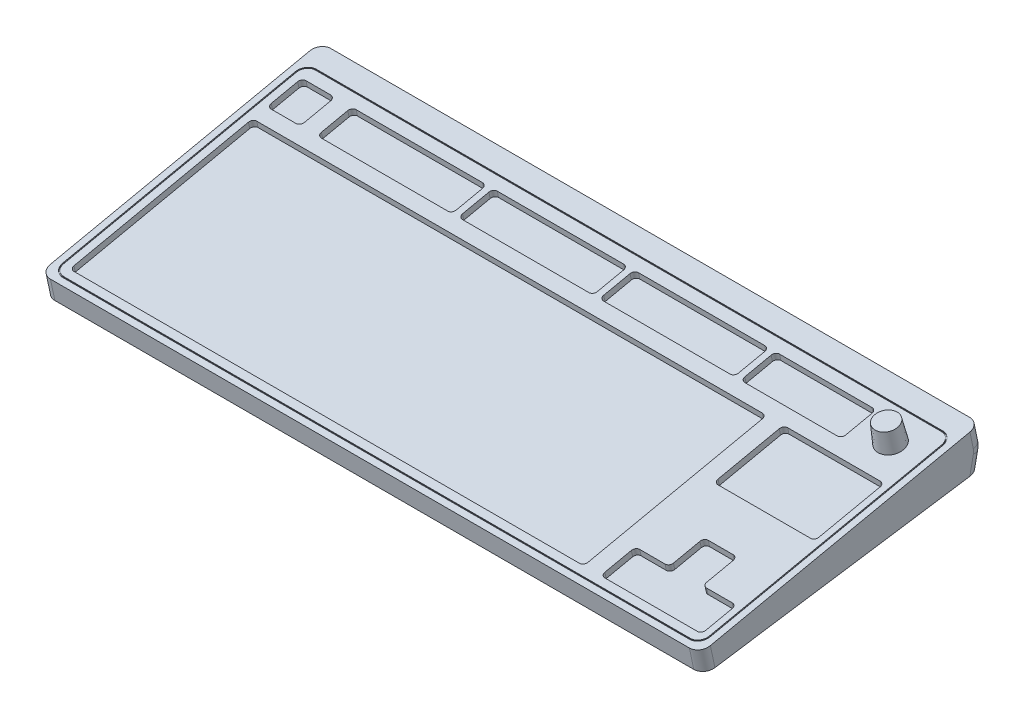
SolidWorks part; units mm, degrees
other "Camera1"
material "ABS"
ref_plane "Front Plane" through (0, 0, 0) normal (0, 0, 1) x (1, 0, 0)
ref_plane "Top Plane" through (0, 0, 0) normal (0, 1, 0) x (1, 0, 0)
ref_plane "Right Plane" through (0, 0, 0) normal (1, 0, 0) x (0, 0, -1)
sketch "Sketch1" plane through (0, 0, 0) normal (0, 1, 0) x (1, 0, 0)
  line L0 (0, 0) -> (128.8917, 0) construction
ref_plane "Plane1" through (0, 0, 0) normal (0, 0.9781, 0.2079) x (1, 0, 0)
sketch "Sketch2" plane through (0, 0, 0) normal (0, 0.9781, 0.2079) x (1, 0, 0)
  line L1 (0, 0) -> (311, 0)
  line L2 (0, 0) -> (0, 135)
  line L3 (0, 135) -> (311, 135)
  line L4 (311, 0) -> (311, 135)
  dimension "D1" = 135
  dimension "D2" = 311
extrude "Boss-Extrude1" add sketch "Sketch2" against normal blind 10
sketch "Sketch5" plane through (0, 0, 0) normal (-1, 0, 0) x (0, 0, 1)
  line L0 (-134.129, 18.2866) -> (-132.3992, 9.7621)
  line L1 (-132.3992, 9.7621) -> (-2.0791, -9.7815)
  line L2 (-2.0791, -9.7815) -> (-134.129, 18.2866)
  dimension "D1" = 110
extrude "Boss-Extrude2" add sketch "Sketch5" against normal blind 311
fillet "Fillet1" radius 10 1 edges at (155.5, 18.2866, -134.129)
fillet "Fillet2" radius 5 8 edges at (0, 13.0064, -133.0575) (311, 13.0064, -133.0575) (311, 18.2856, -133.9155) (0, 18.2856, -133.9155) (311, 24.1933, -132.8735) (0, 24.1933, -132.8735) (311, -4.8907, -1.0396) (0, -4.8907, -1.0396)
sketch "Sketch6" plane through (0, 0, 0) normal (0, 0.9781, 0.2079) x (1, 0, 0)
  line L0 (306, 135) -> (5, 135) construction
  line L5 (8, 3) -> (303, 3)
  line L6 (3, 8) -> (3, 120)
  line L7 (8, 125) -> (303, 125)
  line L8 (308, 8) -> (308, 120)
  line L9 (311, 5) -> (311, 130) construction
  line L10 (0, 130) -> (0, 5) construction
  line L11 (0, 0) -> (128.8917, 0) construction
  arc A2 (15, 10) -> (10, 15) centre (15, 15) cw
  arc A4 (303, 125) -> (308, 120) centre (303, 120) cw
  arc A5 (303, 3) -> (308, 8) centre (303, 8) ccw
  arc A6 (8, 3) -> (3, 8) centre (8, 8) cw
  arc A7 (3, 120) -> (8, 125) centre (8, 120) cw
  dimension "D2" = 3
  dimension "D5" = 5
  dimension "D1" = 10
  dimension "D3" = 3
  dimension "D4" = 3
extrude "Cut-Extrude-Thin1" cut sketch "Sketch6" against normal blind 0.5 thin thin type one direction reverse wall 0.5
sketch "Sketch7" plane through (0, 0, 0) normal (0, 0.9781, 0.2079) x (1, 0, 0)
  line L0 (306, 135) -> (5, 135) construction
  line L1 (9, 119) -> (20.6, 119)
  line L2 (7, 117) -> (7, 104.3)
  line L3 (9, 102.3) -> (20.6, 102.3)
  line L4 (22.6, 117) -> (22.6, 104.3)
  line L5 (0, 130) -> (0, 5) construction
  line L6 (302.6, 24.05) -> (290.675, 24.05)
  line L7 (32.6, 119) -> (92.1, 119)
  line L8 (30.6, 117) -> (30.6, 104.3)
  line L9 (32.6, 102.3) -> (92.1, 102.3)
  line L10 (94.1, 117) -> (94.1, 104.3)
  line L11 (99.1, 119) -> (158.6, 119)
  line L12 (97.1, 117) -> (97.1, 104.3)
  line L13 (99.1, 102.3) -> (158.6, 102.3)
  line L14 (160.6, 117) -> (160.6, 104.3)
  line L15 (165.6, 119) -> (225.1, 119)
  line L16 (163.6, 117) -> (163.6, 104.3)
  line L17 (165.6, 102.3) -> (225.1, 102.3)
  line L18 (227.1, 117) -> (227.1, 104.3)
  line L19 (232.1, 119) -> (275.6, 119)
  line L20 (230.1, 117) -> (230.1, 104.3)
  line L21 (232.1, 102.3) -> (275.6, 102.3)
  line L22 (277.6, 117) -> (277.6, 104.3)
  line L23 (9, 95.3) -> (247.1, 95.3)
  line L24 (7, 93.3) -> (7, 9.3)
  line L25 (9, 7.3) -> (247.1, 7.3)
  line L26 (249.1, 93.3) -> (249.1, 9.3)
  line L27 (259.1, 95.3) -> (302.6, 95.3)
  line L28 (257.1, 93.3) -> (257.1, 63.8)
  line L29 (259.1, 61.8) -> (302.6, 61.8)
  line L30 (304.6, 93.3) -> (304.6, 63.8)
  line L31 (259.1, 7.3) -> (302.6, 7.3)
  line L32 (257.1, 9.3) -> (257.1, 22.05)
  line L33 (275.025, 40.8) -> (286.675, 40.8)
  line L34 (304.6, 9.3) -> (304.6, 22.05)
  line L39 (288.675, 26.05) -> (288.675, 38.8)
  line L40 (259.1, 24.05) -> (271.025, 24.05)
  line L41 (273.025, 26.05) -> (273.025, 38.8)
  arc A3 (302.6, 7.3) -> (304.6, 9.3) centre (302.6, 9.3) ccw
  arc A4 (302.6, 24.05) -> (304.6, 22.05) centre (302.6, 22.05) cw
  arc A5 (290.675, 24.05) -> (288.675, 26.05) centre (290.675, 26.05) cw
  arc A6 (288.675, 38.8) -> (286.675, 40.8) centre (286.675, 38.8) ccw
  arc A7 (273.025, 38.8) -> (275.025, 40.8) centre (275.025, 38.8) cw
  arc A8 (271.025, 24.05) -> (273.025, 26.05) centre (271.025, 26.05) ccw
  arc A9 (259.1, 24.05) -> (257.1, 22.05) centre (259.1, 22.05) ccw
  arc A10 (259.1, 7.3) -> (257.1, 9.3) centre (259.1, 9.3) cw
  arc A11 (247.1, 7.3) -> (249.1, 9.3) centre (247.1, 9.3) ccw
  arc A12 (247.1, 95.3) -> (249.1, 93.3) centre (247.1, 93.3) cw
  arc A14 (302.6, 95.3) -> (304.6, 93.3) centre (302.6, 93.3) cw
  arc A15 (302.6, 61.8) -> (304.6, 63.8) centre (302.6, 63.8) ccw
  arc A16 (257.1, 63.8) -> (259.1, 61.8) centre (259.1, 63.8) ccw
  arc A17 (259.1, 95.3) -> (257.1, 93.3) centre (259.1, 93.3) ccw
  arc A18 (275.6, 119) -> (277.6, 117) centre (275.6, 117) cw
  arc A19 (275.6, 102.3) -> (277.6, 104.3) centre (275.6, 104.3) ccw
  arc A20 (230.1, 104.3) -> (232.1, 102.3) centre (232.1, 104.3) ccw
  arc A21 (232.1, 119) -> (230.1, 117) centre (232.1, 117) ccw
  arc A22 (165.6, 119) -> (163.6, 117) centre (165.6, 117) ccw
  arc A23 (158.6, 119) -> (160.6, 117) centre (158.6, 117) cw
  arc A24 (225.1, 119) -> (227.1, 117) centre (225.1, 117) cw
  arc A25 (225.1, 102.3) -> (227.1, 104.3) centre (225.1, 104.3) ccw
  arc A26 (163.6, 104.3) -> (165.6, 102.3) centre (165.6, 104.3) ccw
  arc A27 (158.6, 102.3) -> (160.6, 104.3) centre (158.6, 104.3) ccw
  arc A28 (7, 9.3) -> (9, 7.3) centre (9, 9.3) ccw
  arc A29 (97.1, 104.3) -> (99.1, 102.3) centre (99.1, 104.3) ccw
  arc A30 (99.1, 119) -> (97.1, 117) centre (99.1, 117) ccw
  arc A31 (92.1, 119) -> (94.1, 117) centre (92.1, 117) cw
  arc A32 (92.1, 102.3) -> (94.1, 104.3) centre (92.1, 104.3) ccw
  arc A33 (30.6, 104.3) -> (32.6, 102.3) centre (32.6, 104.3) ccw
  arc A34 (32.6, 119) -> (30.6, 117) centre (32.6, 117) ccw
  arc A35 (9, 119) -> (7, 117) centre (9, 117) ccw
  arc A36 (20.6, 119) -> (22.6, 117) centre (20.6, 117) cw
  arc A37 (20.6, 102.3) -> (22.6, 104.3) centre (20.6, 104.3) ccw
  arc A38 (7, 104.3) -> (9, 102.3) centre (9, 104.3) ccw
  arc A39 (9, 95.3) -> (7, 93.3) centre (9, 93.3) ccw
  point P32 (230.1, 110.65)
  point P58 (288.675, 24.05)
  point P82 (257.1, 61.8)
  point P85 (257.1, 95.3)
  point P88 (277.6, 119)
  point P95 (230.1, 119)
  point P98 (163.6, 119)
  point P101 (160.6, 119)
  point P104 (227.1, 119)
  point P107 (227.1, 102.3)
  point P114 (7, 7.3)
  point P119 (97.1, 119)
  point P122 (94.1, 119)
  point P129 (30.6, 119)
  point P132 (7, 119)
  point P135 (22.6, 119)
  point P140 (7, 102.3)
  point P143 (7, 95.3)
  dimension "D1" = 16
  dimension "D2" = 7
  dimension "D3" = 16.7
  dimension "D4" = 15.6
  dimension "D5" = 8
  dimension "D6" = 63.5
  dimension "D7" = 3
  dimension "D8" = 63.5
  dimension "D9" = 63.5
  dimension "D10" = 3
  dimension "D11" = 16.7
  dimension "D12" = 47.5
  dimension "D13" = 7
  dimension "D14" = 88
  dimension "D15" = 33.5
  dimension "D16" = 8
  dimension "D17" = 0
  dimension "D18" = 3
  dimension "D20" = 8
  dimension "D23" = 15.65
  dimension "D24" = 15.925
  dimension "D25" = 16.7
  dimension "16" = 16
extrude "Cut-Extrude1" cut sketch "Sketch7" against normal blind 3
sketch "Sketch8" plane through (0, 0, 0) normal (0, 0.9781, 0.2079) x (1, 0, 0)
  line L0 (277.6, 110.65) -> (307.5, 110.65) construction
  line L1 (277.6, 104.3) -> (277.6, 117) construction
  line L2 (307.5, 8) -> (307.5, 120) construction
  circle A0 centre (292.55, 110.65) radius 6
extrude "Boss-Extrude3" add sketch "Sketch8" along normal blind 10 draft 4
